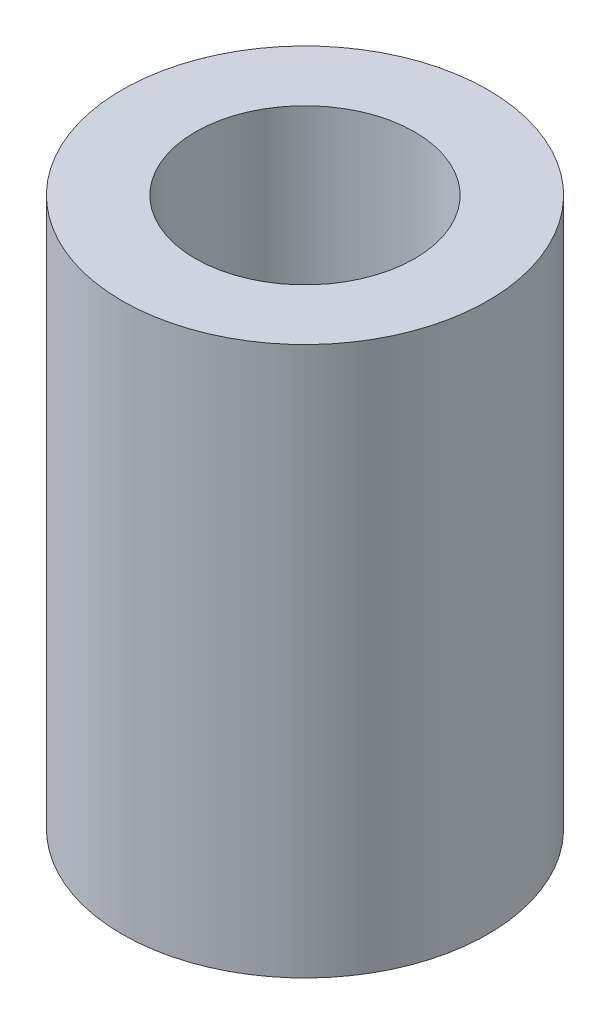
SolidWorks part; units mm, degrees
material "AISI 1020"
ref_plane "Спереди" through (0, 0, 0) normal (0, 0, 1) x (1, 0, 0)
ref_plane "Сверху" through (0, 0, 0) normal (0, 1, 0) x (1, 0, 0)
ref_plane "Справа" through (0, 0, 0) normal (1, 0, 0) x (0, 0, -1)
sketch "Эскиз1" plane through (0, 0, 0) normal (0, 1, 0) x (1, 0, 0)
  line L0 (0, 0) -> (-492.5, 0) construction
  line L1 (0, 3) -> (0, 47) construction
  circle A0 centre (-10, -10) radius 10
  circle A1 centre (-10, -10) radius 6
  dimension "D1" = 12
  dimension "D2" = 4
extrude "Бобышка-Вытянуть1" add sketch "Эскиз1" along normal blind 30
